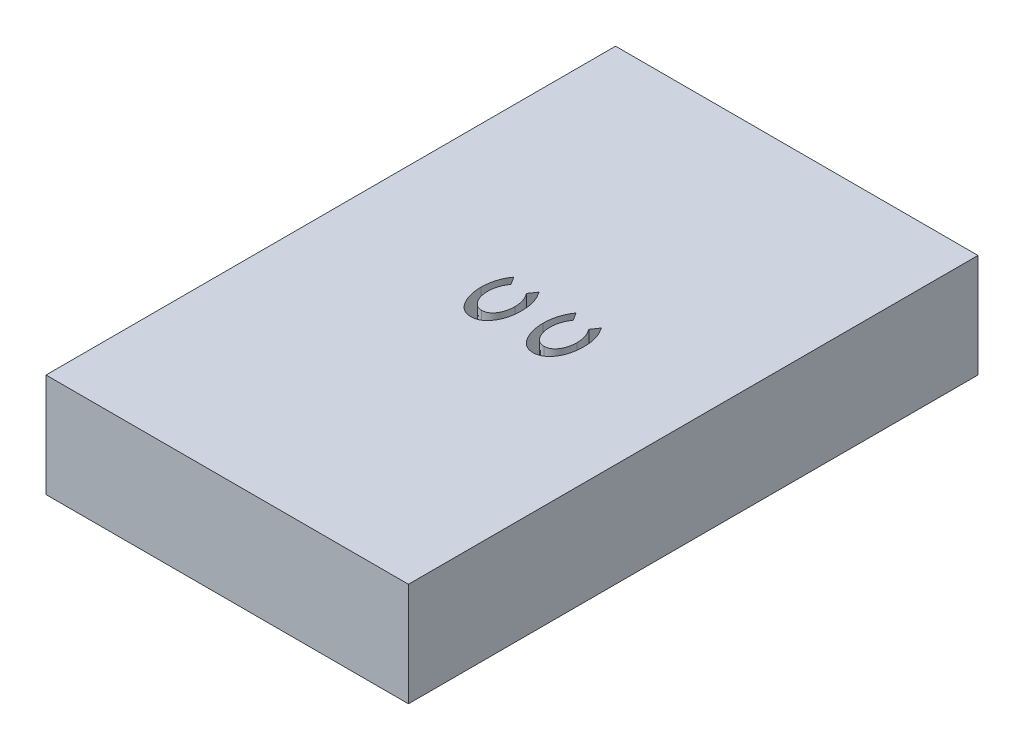
SolidWorks part; units mm, degrees
ref_plane "Front Plane" through (0, 0, 0) normal (0, 0, 1) x (1, 0, 0)
ref_plane "Top Plane" through (0, 0, 0) normal (0, 1, 0) x (1, 0, 0)
ref_plane "Right Plane" through (0, 0, 0) normal (1, 0, 0) x (0, 0, -1)
sketch "Sketch1" plane through (0, 0, 0) normal (0, 1, 0) x (1, 0, 0)
  line L1 (0, 0) -> (88.9, 0)
  line L2 (0, 0) -> (0, 139.7)
  line L3 (0, 139.7) -> (88.9, 139.7)
  line L4 (88.9, 0) -> (88.9, 139.7)
  dimension "D1" = 139.7
  dimension "D2" = 88.9
extrude "Boss-Extrude1" add sketch "Sketch1" along normal blind 25.4
sketch "Sketch2" plane through (0, 25.4, 0) normal (0, 1, 0) x (1, 0, 0)
  line L0 (0, 139.7) -> (0, 0) construction
  line L1 (88.9, 139.7) -> (0, 139.7) construction
  text T0 "<b><r90>CC</r></b>" font "Century Gothic" height in points 36
  dimension "D1" = 44.45
  dimension "D2" = 76.2
extrude "Cut-Extrude1" cut sketch "Sketch2" against normal through all
